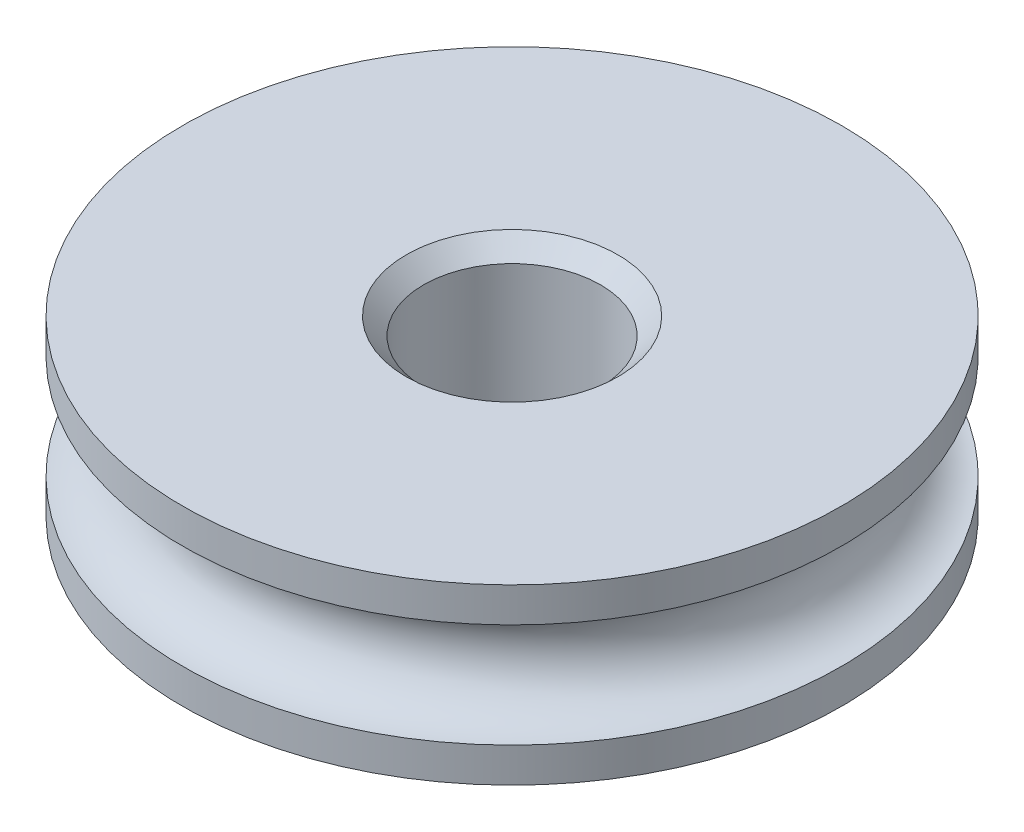
SolidWorks part; units mm, degrees
ref_plane "Front Plane" through (0, 0, 0) normal (0, 0, 1) x (1, 0, 0)
ref_plane "Top Plane" through (0, 0, 0) normal (0, 1, 0) x (1, 0, 0)
ref_plane "Right Plane" through (0, 0, 0) normal (1, 0, 0) x (0, 0, -1)
sketch "Sketch1" plane through (0, 0, 0) normal (1, 0, 0) x (0, 0, -1)
  line L0 (0, 0) -> (24.13, 0)
  line L1 (24.13, 0) -> (24.13, 2.54)
  line L2 (0, 0) -> (0, 12.7)
  line L3 (24.13, 10.16) -> (24.13, 12.7)
  line L4 (24.13, 12.7) -> (0, 12.7)
  arc A2 (24.13, 10.16) -> (24.13, 2.54) centre (24.13, 6.35) ccw
  point P8 (0, 0)
  dimension "D1" = 24.13
  dimension "D2" = 12.7
  dimension "D3" = 2.54
revolve "Revolve1" add sketch "Sketch1" angle 360 about L2
sketch "Sketch2" plane through (0, 0, 0) normal (0, -1, 0) x (1, 0, 0)
  circle A0 centre (0, 0) radius 6.477
  dimension "D1" = 12.954
extrude "Cut-Extrude1" cut sketch "Sketch2" against normal through all
chamfer "Chamfer1" distance 1.27 angle 45 2 edges at (0, 12.7, -6.477) (0, 0, -6.477)
